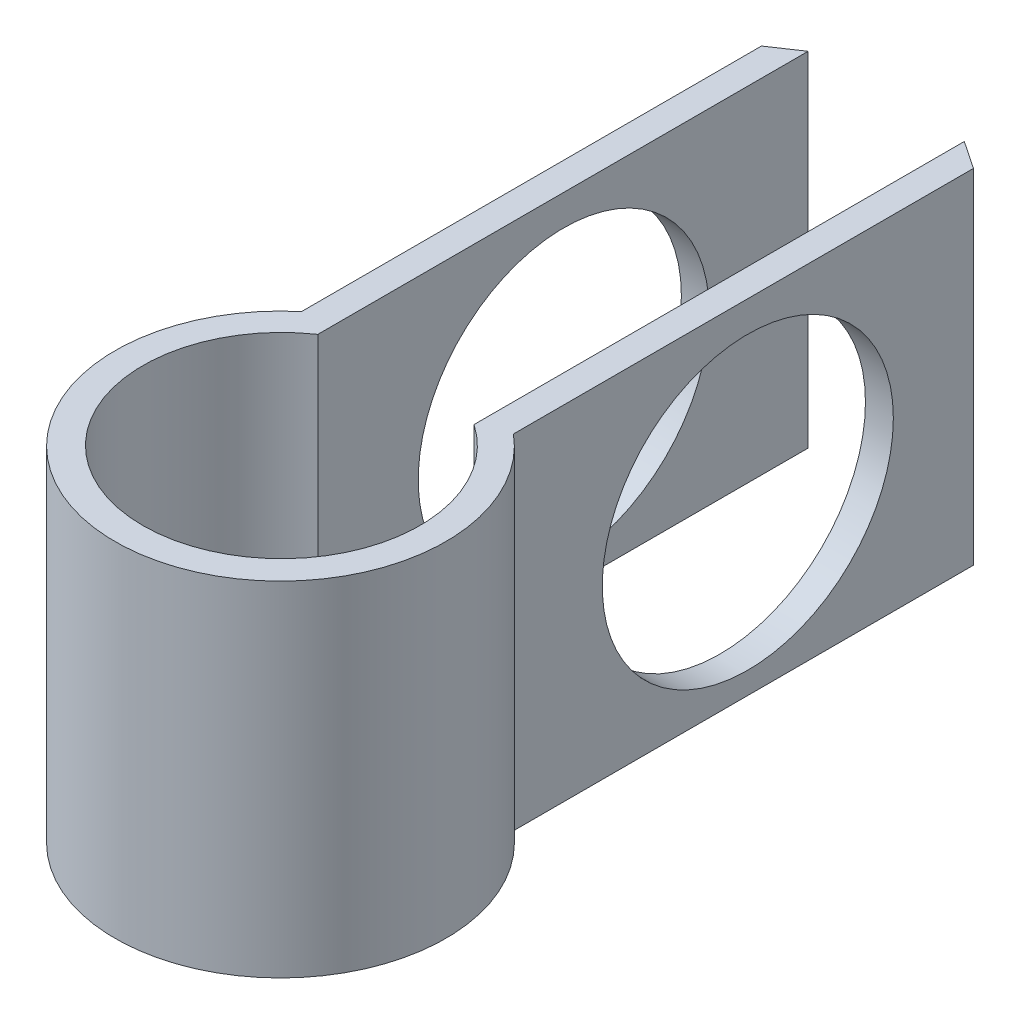
SolidWorks part; units mm, degrees
ref_plane "Front Plane" through (0, 0, 0) normal (0, 0, 1) x (1, 0, 0)
ref_plane "Top Plane" through (0, 0, 0) normal (0, 1, 0) x (1, 0, 0)
ref_plane "Right Plane" through (0, 0, 0) normal (1, 0, 0) x (0, 0, -1)
sketch "Sketch1" plane through (0, 0, 0) normal (0, 1, 0) x (1, 0, 0)
  line L0 (136.2502, 107.2599) -> (136.2502, 64.9887)
  line L1 (136.2502, 107.2599) -> (133.6883, 108.9792)
  line L2 (133.6883, 108.9792) -> (133.6883, 63.9257)
  line L3 (119.3348, 108.9792) -> (116.7729, 107.2599)
  line L4 (116.7729, 107.2599) -> (116.7729, 64.9887)
  line L5 (119.3348, 108.9792) -> (119.3348, 63.9257)
  arc A0 (116.7729, 64.9887) -> (136.2502, 64.9887) centre (126.5116, 53.3186) ccw
  arc A1 (119.3348, 63.9257) -> (133.6883, 63.9257) centre (126.5116, 53.4056) ccw
  point P6 (126.5116, 40.6707)
  point P9 (126.5116, 38.1188)
extrude "Boss-Extrude1" add sketch "Sketch1" against normal blind 31.5798
sketch "Sketch2" plane through (136.2502, 0, 0) normal (1, 0, 0) x (0, 0, -1)
  line L0 (107.2599, -31.5798) -> (107.2599, 0) construction
  line L2 (64.9887, 0) -> (107.2599, 0) construction
  circle A0 centre (86.5243, -16.1958) radius 13.3728
  point P6 (99.4415, -12.7348)
  dimension "D1" = 20.7355
  dimension "D2" = 16.1958
  dimension "D3" = 12.7348
  dimension "D4" = 7.8184
extrude "Cut-Extrude1" cut sketch "Sketch2" against normal through all
move or copy body "Body-Move/Copy1" [suppressed] bodies to move or copy 102
